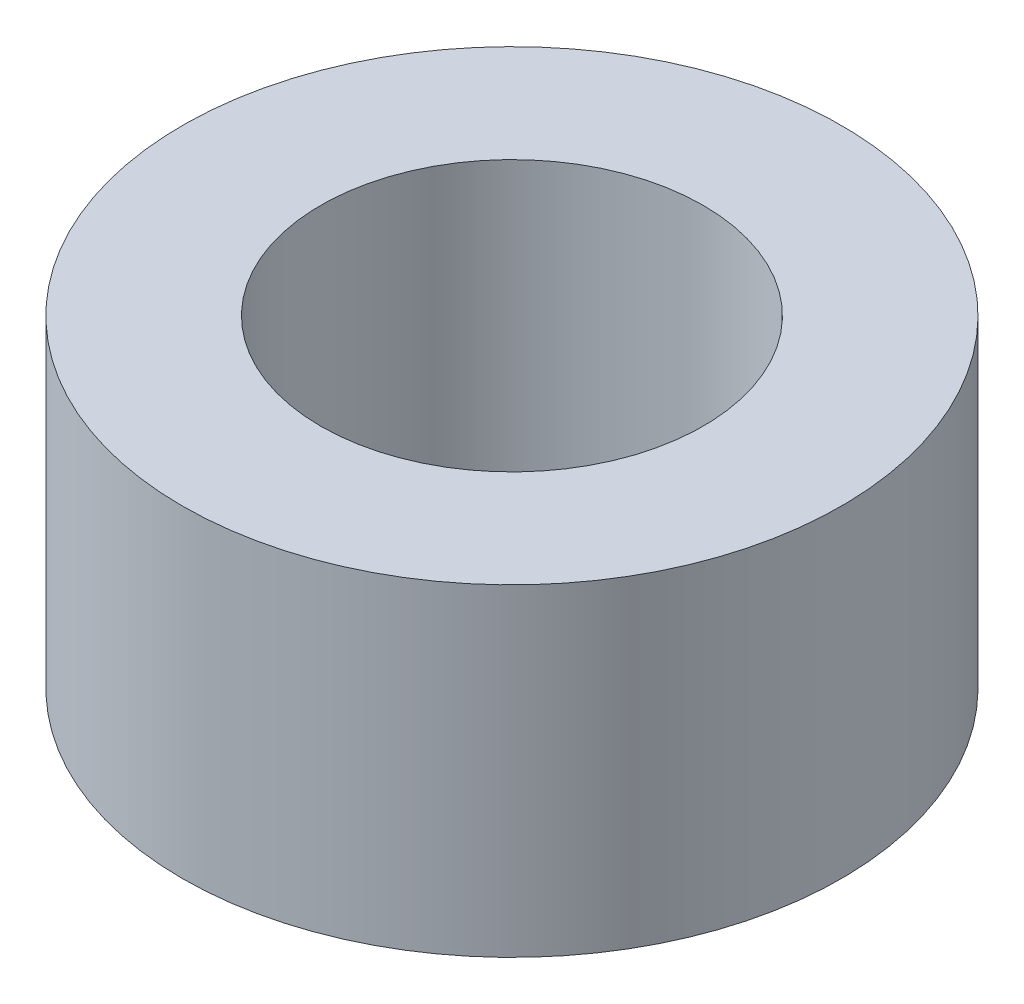
SolidWorks part; units mm, degrees
ref_plane "Front Plane" through (0, 0, 0) normal (0, 0, 1) x (1, 0, 0)
ref_plane "Top Plane" through (0, 0, 0) normal (0, 1, 0) x (1, 0, 0)
ref_plane "Right Plane" through (0, 0, 0) normal (1, 0, 0) x (0, 0, -1)
sketch "Sketch1" plane through (0, 0, 0) normal (0, 1, 0) x (1, 0, 0)
  circle A0 centre (0, 0) radius 4.15
  circle A1 centre (0, 0) radius 7.15
  dimension "D1" = 8.3
  dimension "D2" = 3
extrude "Boss-Extrude1" add sketch "Sketch1" along normal blind 7
